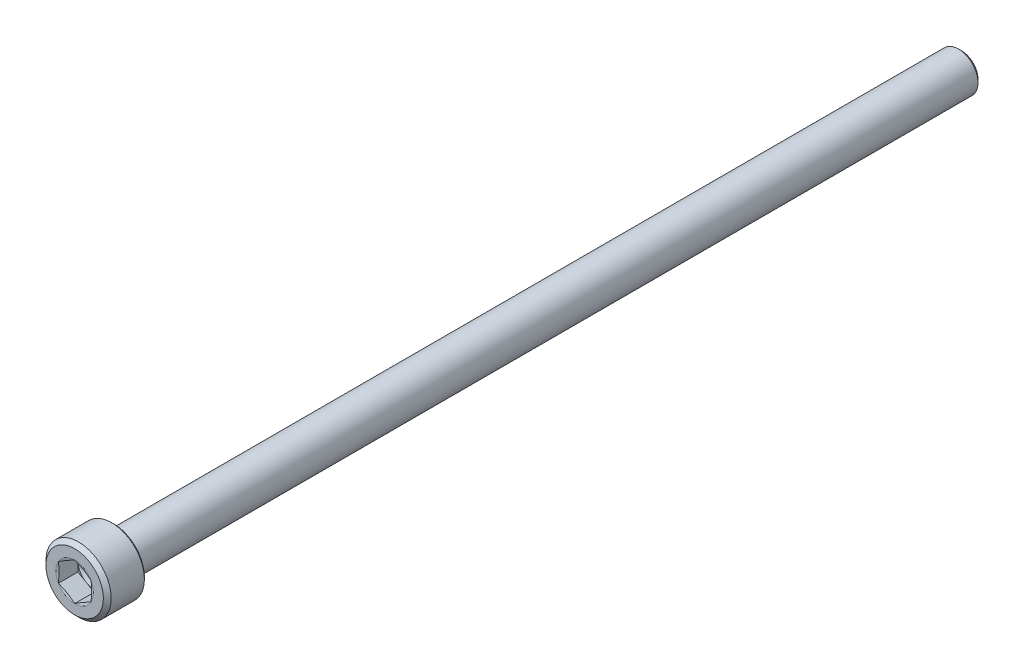
SolidWorks part; units mm, degrees
ref_plane "Front Plane" through (0, 0, 0) normal (0, 0, 1) x (1, 0, 0)
ref_plane "Top Plane" through (0, 0, 0) normal (0, 1, 0) x (1, 0, 0)
ref_plane "Right Plane" through (0, 0, 0) normal (1, 0, 0) x (0, 0, -1)
sketch "Sketch1" plane through (0, 0, 0) normal (1, 0, 0) x (0, 0, -1)
  line L0 (0, 0) -> (12.9407, 0) construction
  line L1 (0, 0) -> (0, 4.4)
  line L2 (0, 4.4) -> (0.6, 5)
  line L3 (0.6, 5) -> (5.69, 5)
  line L4 (6, 4.69) -> (6, 3.4)
  line L5 (6.68, 3) -> (135.5, 3)
  line L6 (135.5, 3) -> (136, 2.5)
  line L7 (136, 2.5) -> (136, 0)
  line L8 (136, 0) -> (0, 0)
  line L9 (5.69, 5) -> (6, 4.69)
  line L10 (6.5977, 3.0139) -> (6.1677, 3.1639)
  arc A2 (6.68, 3) -> (6.5977, 3.0139) centre (6.68, 3.25) cw
  arc A3 (6.1677, 3.1639) -> (6, 3.4) centre (6.25, 3.4) cw
  point P6 (6, 5)
  dimension "R2" = 0.25
  dimension "R1" = 0.25
  dimension "D1" = 45
  dimension "DK" = 10
  dimension "D3" = 45
  dimension "length" = 130
  dimension "K" = 6
  dimension "V" = 0.6
  dimension "HOLESIZE" = 6
  dimension "D4" = 5
  dimension "D5" = 45
  dimension "DW" = 9.38
  dimension "F" = 0.68
  dimension "DA" = 6.8
revolve "Revolve1" add sketch "Sketch1" angle 360 about L0
cosmetic thread "Cosmetic Thread1" parameters "D1"=94, "D2"=6
sketch "Sketch2" plane through (0, 0, 0) normal (0, 0, 1) x (1, 0, 0)
  line L0 (0, 0) -> (0, 2.8868) construction
  line L2 (0, 2.8868) -> (-2.5, 1.4434)
  line L3 (-2.5, 1.4434) -> (-2.5, -1.4434)
  line L4 (-2.5, -1.4434) -> (0, -2.8868)
  line L5 (0, -2.8868) -> (2.5, -1.4434)
  line L6 (2.5, -1.4434) -> (2.5, 1.4434)
  line L7 (2.5, 1.4434) -> (0, 2.8868)
  circle A0 centre (0, 0) radius 2.5 construction
  dimension "S" = 5
extrude "Cut-Extrude1" cut sketch "Sketch2" against normal blind 3
sketch "Sketch3" plane through (0, 0, 0) normal (1, 0, 0) x (0, 0, -1)
  line L0 (3, 0) -> (136, 0) construction
  line L1 (136, -2.5) -> (136, 2.5) construction
  line L2 (3, 0) -> (3, 2.5)
  line L4 (3, 2.5) -> (4.4434, 0)
  line L5 (4.4434, 0) -> (3, 0)
  line L6 (0, 4.4) -> (0, -4.4) construction
  dimension "DRILLANG" = 60
  dimension "DRILL DEPTH" = 3
  dimension "S2" = 5
revolve "Cut-Revolve2" cut sketch "Sketch3" angle 360 about L0
sketch "Sketch4" plane through (0, 0, 0) normal (1, 0, 0) x (0, 0, -1)
  line L0 (0, 0) -> (4.6121, 0) construction
  line L1 (0, 2.8868) -> (0, 2.5)
  line L2 (0, 4.4) -> (0, -4.4) construction
  line L3 (0, 2.5) -> (0.1036, 2.5)
  line L4 (0.1036, 2.5) -> (0, 2.8868)
  point P12 (0.0518, 2.5)
  dimension "D1" = 5
  dimension "D2" = 15
revolve "Cut-Revolve3" cut sketch "Sketch4" angle 360 about L0
